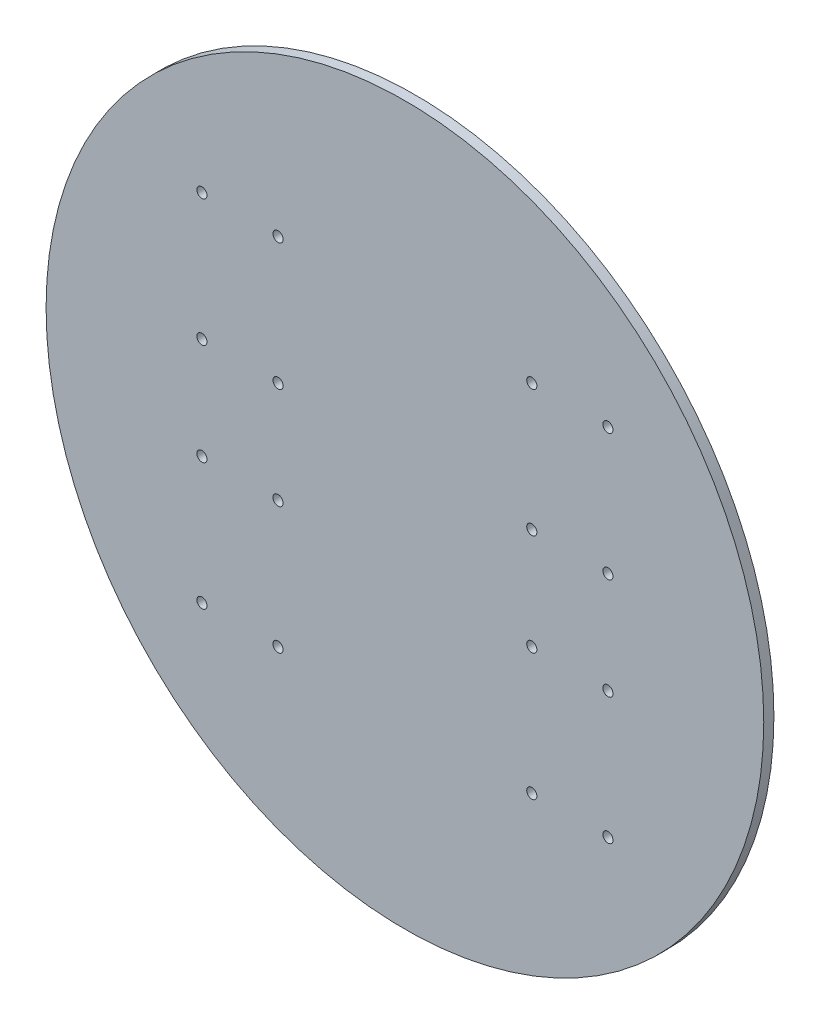
SolidWorks part; units mm, degrees
ref_plane "正面" through (0, 0, 0) normal (0, 0, 1) x (1, 0, 0)
ref_plane "平面" through (0, 0, 0) normal (0, 1, 0) x (1, 0, 0)
ref_plane "右側面" through (0, 0, 0) normal (1, 0, 0) x (0, 0, -1)
sketch "ｽｹｯﾁ1" plane through (0, 0, 0) normal (0, 0, 1) x (1, 0, 0)
  line L1 (50, -50) -> (-50, -50) construction
  line L2 (50, -50) -> (50, 50) construction
  line L3 (50, 50) -> (-50, 50) construction
  line L4 (-50, -50) -> (-50, 50) construction
  line L5 (50, -50) -> (-50, 50) construction
  line L6 (50, 50) -> (-50, -50) construction
  circle A0 centre (0, 0) radius 70.7107
  point P0 (0, 0)
  dimension "D1" = 100
  dimension "D2" = 100
extrude "ﾎﾞｽ - 押し出し1" add sketch "ｽｹｯﾁ1" along normal blind 2 contours A0
sketch "ｽｹｯﾁ2" plane through (0, 0, 0) normal (0, 0, 1) x (1, 0, 0)
  line L1 (40, -35) -> (25, -35) construction
  line L2 (40, -35) -> (40, -10) construction
  line L3 (40, -10) -> (25, -10) construction
  line L4 (25, -35) -> (25, -10) construction
  line L5 (40, -35) -> (25, -10) construction
  line L6 (40, -10) -> (25, -35) construction
  line L11 (50, -50) -> (50, 50) construction
  line L13 (50, -50) -> (-50, -50) construction
  circle A0 centre (25, -10) radius 1
  circle A1 centre (40, -10) radius 1
  circle A2 centre (25, -35) radius 1
  circle A3 centre (40, -35) radius 1
  point P0 (32.5, -22.5)
  point P9 (38.4448, -22.5)
  dimension "D1" = 2
  dimension "D2" = 25
  dimension "D3" = 15
  dimension "D4" = 10
  dimension "D5" = 15
extrude "ｶｯﾄ - 押し出し4" cut sketch "ｽｹｯﾁ2" against normal through all both and the other way through all
mirror "ﾐﾗｰ2" about plane through (0, 0, 0) normal (1, 0, 0) of "ｶｯﾄ - 押し出し4"
mirror "ﾐﾗｰ6" about plane through (0, 0, 0) normal (0, 1, 0) of "ﾐﾗｰ2", "ｶｯﾄ - 押し出し4"
